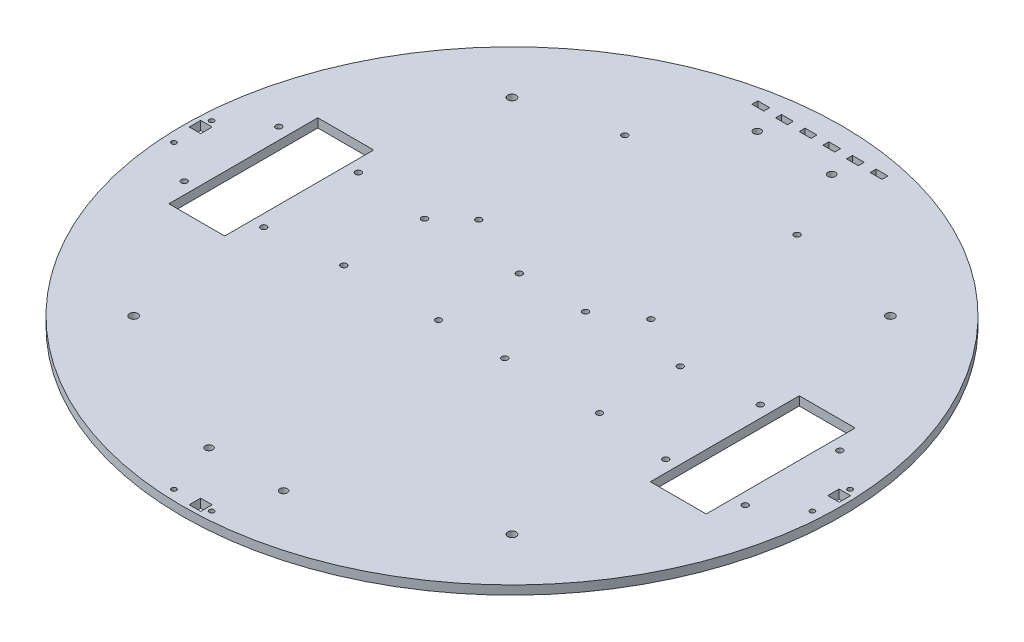
SolidWorks part; units mm, degrees
ref_plane "Front Plane" through (0, 0, 0) normal (0, 0, 1) x (1, 0, 0)
ref_plane "Top Plane" through (0, 0, 0) normal (0, 1, 0) x (1, 0, 0)
ref_plane "Right Plane" through (0, 0, 0) normal (1, 0, 0) x (0, 0, -1)
sketch "Sketch1" plane through (0, 0, 0) normal (0, 1, 0) x (1, 0, 0)
  line L0 (168.375, 7.335) -> (174.525, 7.335)
  line L1 (-144.3, 40) -> (-114.3, 40)
  line L2 (-144.3, 40) -> (-144.3, -40)
  line L3 (-144.3, -40) -> (-114.3, -40)
  line L4 (-114.3, 40) -> (-114.3, -40)
  line L13 (114.3, 40) -> (144.3, 40)
  line L14 (114.3, 40) -> (114.3, -40)
  line L15 (114.3, -40) -> (144.3, -40)
  line L16 (144.3, 40) -> (144.3, -40)
  line L17 (1.185, -168.375) -> (7.335, -168.375)
  line L18 (1.185, -168.375) -> (1.185, -174.525)
  line L19 (1.185, -174.525) -> (7.335, -174.525)
  line L20 (7.335, -168.375) -> (7.335, -174.525)
  line L21 (168.375, 7.335) -> (168.375, 1.185)
  line L22 (168.375, 1.185) -> (174.525, 1.185)
  line L23 (174.525, 7.335) -> (174.525, 1.185)
  line L24 (-174.525, 7.335) -> (-168.375, 7.335)
  line L25 (-174.525, 7.335) -> (-174.525, 1.185)
  line L26 (-174.525, 1.185) -> (-168.375, 1.185)
  line L27 (-168.375, 7.335) -> (-168.375, 1.185)
  line L28 (-21.295, 162.8645) -> (-14.945, 162.8645)
  line L29 (-33.995, 166.0395) -> (-27.645, 166.0395)
  line L30 (-33.995, 166.0395) -> (-33.995, 162.8645)
  line L31 (-33.995, 162.8645) -> (-27.645, 162.8645)
  line L32 (-27.645, 166.0395) -> (-27.645, 162.8645)
  line L33 (-14.945, 166.0395) -> (-14.945, 162.8645)
  line L34 (-21.295, 166.0395) -> (-14.945, 166.0395)
  line L35 (-21.295, 166.0395) -> (-21.295, 162.8645)
  line L36 (-8.595, 162.8645) -> (-2.245, 162.8645)
  line L37 (-2.245, 166.0395) -> (-2.245, 162.8645)
  line L38 (-8.595, 166.0395) -> (-2.245, 166.0395)
  line L39 (-8.595, 166.0395) -> (-8.595, 162.8645)
  line L40 (4.105, 162.8645) -> (10.455, 162.8645)
  line L41 (10.455, 166.0395) -> (10.455, 162.8645)
  line L42 (4.105, 166.0395) -> (10.455, 166.0395)
  line L43 (4.105, 166.0395) -> (4.105, 162.8645)
  line L44 (16.805, 162.8645) -> (23.155, 162.8645)
  line L45 (23.155, 166.0395) -> (23.155, 162.8645)
  line L46 (16.805, 166.0395) -> (23.155, 166.0395)
  line L47 (16.805, 166.0395) -> (16.805, 162.8645)
  line L48 (29.505, 162.8645) -> (35.855, 162.8645)
  line L49 (35.855, 166.0395) -> (35.855, 162.8645)
  line L50 (29.505, 166.0395) -> (35.855, 166.0395)
  line L51 (29.505, 166.0395) -> (29.505, 162.8645)
  circle A0 centre (0, 0) radius 177
  circle A1 centre (-150.65, 25.4) radius 1.6
  circle A2 centre (-150.65, -25.4) radius 1.6
  circle A3 centre (150.65, 25.4) radius 1.6
  circle A4 centre (150.65, -25.4) radius 1.6
  circle A5 centre (-107.95, 25.4) radius 1.6
  circle A6 centre (-107.95, -25.4) radius 1.6
  circle A7 centre (107.95, 25.4) radius 1.6
  circle A8 centre (107.95, -25.4) radius 1.6
  circle A9 centre (-53.7, 114.3) radius 1.6
  circle A10 centre (38.8, 114.3) radius 1.6
  circle A11 centre (-53.7, 35.8) radius 1.6
  circle A12 centre (38.8, 35.8) radius 1.6
  circle A13 centre (-101.6, -101.6) radius 2.2479
  circle A14 centre (101.6, -101.6) radius 2.2479
  circle A15 centre (-101.6, 101.6) radius 2.2479
  circle A16 centre (101.6, 101.6) radius 2.2479
  circle A17 centre (-20, -142.687) radius 2
  circle A18 centre (20, -142.687) radius 2
  circle A19 centre (-20, 151.7193) radius 2
  circle A20 centre (20, 151.7193) radius 2
  circle A21 centre (-10.125, -171.45) radius 1.3
  circle A22 centre (10.125, -171.45) radius 1.3
  circle A23 centre (171.45, -10.125) radius 1.3
  circle A24 centre (171.45, 10.125) radius 1.3
  circle A25 centre (-171.45, -10.125) radius 1.3
  circle A26 centre (-171.45, 10.125) radius 1.3
  point P9 (-114.3, 0)
  point P10 (-0.9618, 0)
  point P11 (-0.9618, 0)
  point P14 (114.3, 0)
  point P26 (-144.3, 0)
  point P27 (144.3, 0)
  dimension "D1" = 354
  dimension "D10" = 3.2
  dimension "D12" = 6.35
  dimension "D13" = 3.2
  dimension "D16" = 6.35
  dimension "D17" = 50.8
  dimension "D20" = 3.2
  dimension "D22" = 3.2
  dimension "D23" = 6.35
  dimension "D24" = 50.8
  dimension "D25" = 25.4
  dimension "D26" = 3.2
  dimension "D27" = 3.2
  dimension "D32" = 3.2
  dimension "D33" = 3.2
  dimension "D34" = 3.2
  dimension "D35" = 3.2
  dimension "D44" = 4.4958
  dimension "D45" = 4.4958
  dimension "D46" = 4.4958
  dimension "D47" = 4.4958
  dimension "D55" = 4
  dimension "D56" = 4
  dimension "D59" = 20
  dimension "D60" = 4
  dimension "D61" = 4
  dimension "D62" = 0
  dimension "D63" = 40
  dimension "D64" = 20
  dimension "D65" = 2.6
  dimension "D66" = 2.6
  dimension "D74" = 171.45
  dimension "D75" = 2.6
  dimension "D76" = 2.6
  dimension "D77" = 0
  dimension "D87" = 2.6
  dimension "D88" = 2.6
  dimension "D90" = 2.79
  dimension "D92" = 0
  dimension "D122" = 3.2
  dimension "D123" = 3.2
  dimension "D2" = 30
  dimension "D3" = 80
  dimension "D4" = 0
  dimension "D5" = 114.3
  dimension "D6" = 30
  dimension "D7" = 80
  dimension "D8" = 0
  dimension "D9" = 114.3
  dimension "D11" = 50.8
  dimension "D14" = 6.35
  dimension "D15" = 25.4
  dimension "D18" = 25.4
  dimension "D19" = 6.35
  dimension "D21" = 6.35
  dimension "D28" = 50.8
  dimension "D29" = 6.35
  dimension "D30" = 6.35
  dimension "D31" = 25.4
  dimension "D36" = 78.5
  dimension "D37" = 78.5
  dimension "D38" = 92.5
  dimension "D39" = 92.5
  dimension "D40" = 0
  dimension "D41" = 0
  dimension "D42" = 38.8
  dimension "D43" = 114.3
  dimension "D48" = 203.2
  dimension "D49" = 203.2
  dimension "D50" = 203.2
  dimension "D51" = 203.2
  dimension "D52" = 0
  dimension "D53" = 101.6
  dimension "D54" = 101.6
  dimension "D57" = 40
  dimension "D58" = 0
  dimension "D67" = 0
  dimension "D68" = 20.25
  dimension "D69" = 10.125
  dimension "D70" = 6.15
  dimension "D71" = 6.15
  dimension "D72" = 2.79
  dimension "D73" = 3.075
  dimension "D78" = 20.25
  dimension "D79" = 10.125
  dimension "D80" = 6.15
  dimension "D81" = 6.15
  dimension "D82" = 2.79
  dimension "D83" = 3.075
  dimension "D84" = 171.45
  dimension "D85" = 6.15
  dimension "D86" = 6.15
  dimension "D89" = 20.25
  dimension "D91" = 3.075
  dimension "D93" = 171.45
  dimension "D94" = 10.125
  dimension "D95" = 3.175
  dimension "D96" = 6.35
  dimension "D97" = 6
extrude "Boss-Extrude1" add sketch "Sketch1" along normal blind 4.7625
sketch "Sketch2" plane through (0, 4.7625, 0) normal (0, 1, 0) x (1, 0, 0)
  circle A4 centre (17.78, 21.69) radius 1.6
  circle A5 centre (17.78, -21.69) radius 1.6
  circle A6 centre (68.66, -21.69) radius 1.6
  circle A7 centre (68.66, 21.69) radius 1.6
  circle A12 centre (-68.66, 21.69) radius 1.6
  circle A13 centre (-68.66, -21.69) radius 1.6
  circle A14 centre (-17.78, -21.69) radius 1.6
  circle A15 centre (-17.78, 21.69) radius 1.6
  point P17 (-22.0657, -30.3431)
  point P18 (-32.967, -16.0736)
  point P19 (-61.5737, -39.8578)
  dimension "D3" = 3.2
  dimension "D4" = 3.2
  dimension "D5" = 3.2
  dimension "D6" = 3.2
  dimension "D7" = 3.2
  dimension "D8" = 3.2
  dimension "D9" = 3.2
  dimension "D10" = 3.2
  dimension "D11" = 50.88
  dimension "D12" = 50.88
  dimension "D13" = 0
  dimension "D14" = 0
  dimension "D22" = 21.69
  dimension "D26" = 17.78
  dimension "D15" = 43.38
  dimension "D16" = 50.88
  dimension "D17" = 50.88
  dimension "D18" = 0
  dimension "D19" = 0
  dimension "D20" = 43.38
  dimension "D21" = 0
  dimension "D23" = 0
  dimension "D24" = 21.69
  dimension "D25" = 17.78
extrude "Cut-Extrude1" cut sketch "Sketch2" against normal through all
